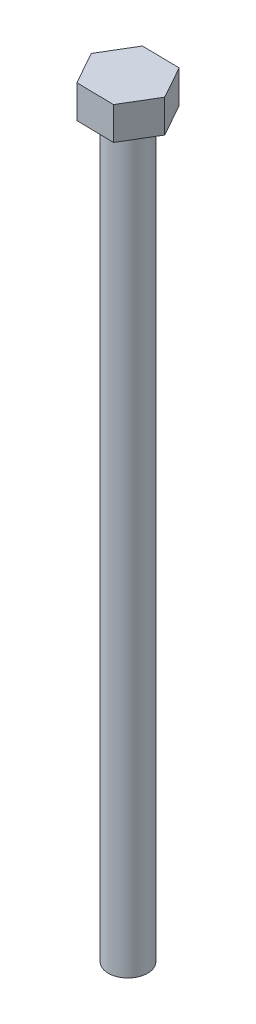
SolidWorks part; units mm, degrees
ref_plane "Front Plane" through (0, 0, 0) normal (0, 0, 1) x (1, 0, 0)
ref_plane "Top Plane" through (0, 0, 0) normal (0, 1, 0) x (1, 0, 0)
ref_plane "Right Plane" through (0, 0, 0) normal (1, 0, 0) x (0, 0, -1)
sketch "Sketch1" plane through (0, 0, 0) normal (0, 1, 0) x (1, 0, 0)
  circle A0 centre (0, 0) radius 3
extrude "Boss-Extrude1" add sketch "Sketch1" along normal blind 112
sketch "Sketch2" plane through (0, 112, 0) normal (0, 1, 0) x (1, 0, 0)
  line L1 (2.9177, 4.8762) -> (-2.7641, 4.9649)
  line L2 (-2.7641, 4.9649) -> (-5.6818, 0.0887)
  line L3 (-5.6818, 0.0887) -> (-2.9177, -4.8762)
  line L4 (-2.9177, -4.8762) -> (2.7641, -4.9649)
  line L5 (2.7641, -4.9649) -> (5.6818, -0.0887)
  line L6 (5.6818, -0.0887) -> (2.9177, 4.8762)
  circle A0 centre (0, 0) radius 4.9211 construction
extrude "Boss-Extrude2" add sketch "Sketch2" along normal blind 5
